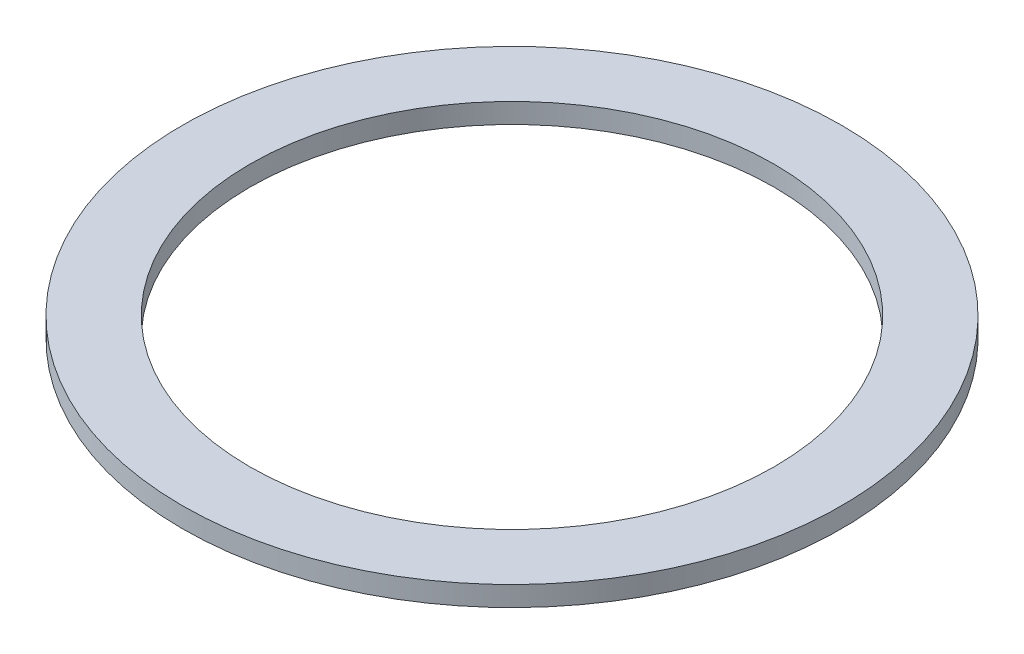
SolidWorks part; units mm, degrees
ref_plane "前视基准面" through (0, 0, 0) normal (0, 0, 1) x (1, 0, 0)
ref_plane "上视基准面" through (0, 0, 0) normal (0, 1, 0) x (1, 0, 0)
ref_plane "右视基准面" through (0, 0, 0) normal (1, 0, 0) x (0, 0, -1)
sketch "Sketch1" plane through (0, 0, 0) normal (0, 1, 0) x (1, 0, 0)
  circle A0 centre (0, 0) radius 26.25
  circle A1 centre (0, 0) radius 33
  dimension "D1" = 52.5
extrude "Boss-Extrude1" add sketch "Sketch1" along normal blind 2
